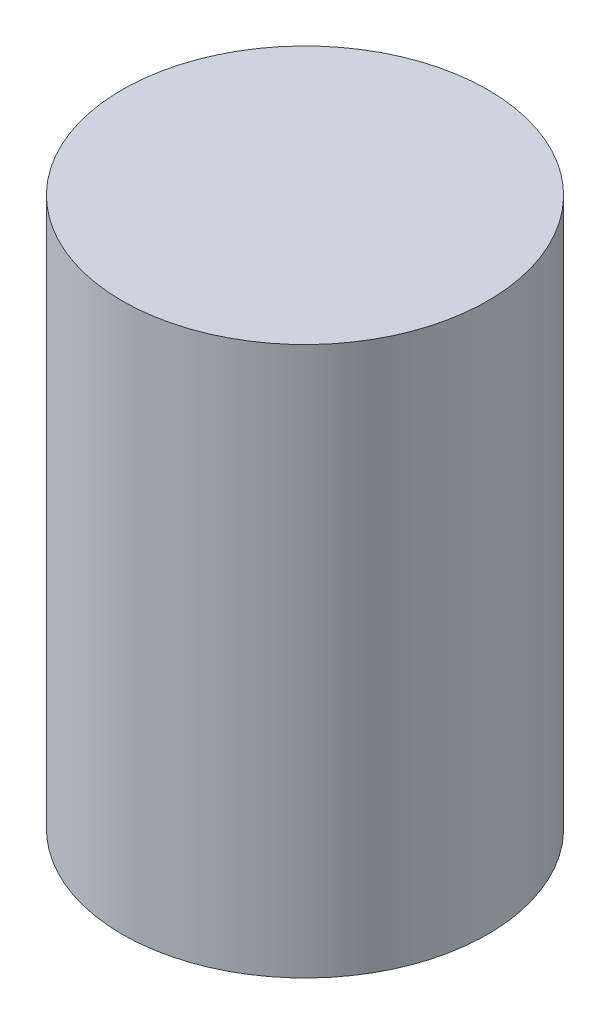
SolidWorks part; units mm, degrees
ref_plane "前视基准面" through (0, 0, 0) normal (0, 0, 1) x (1, 0, 0)
ref_plane "上视基准面" through (0, 0, 0) normal (0, 1, 0) x (1, 0, 0)
ref_plane "右视基准面" through (0, 0, 0) normal (1, 0, 0) x (0, 0, -1)
other "Configuration Table"
sketch "草图1" plane through (0, 0, 0) normal (0, 1, 0) x (1, 0, 0)
  circle A0 centre (0, 0) radius 10
extrude "凸台-拉伸1" add sketch "草图1" along normal blind 30
